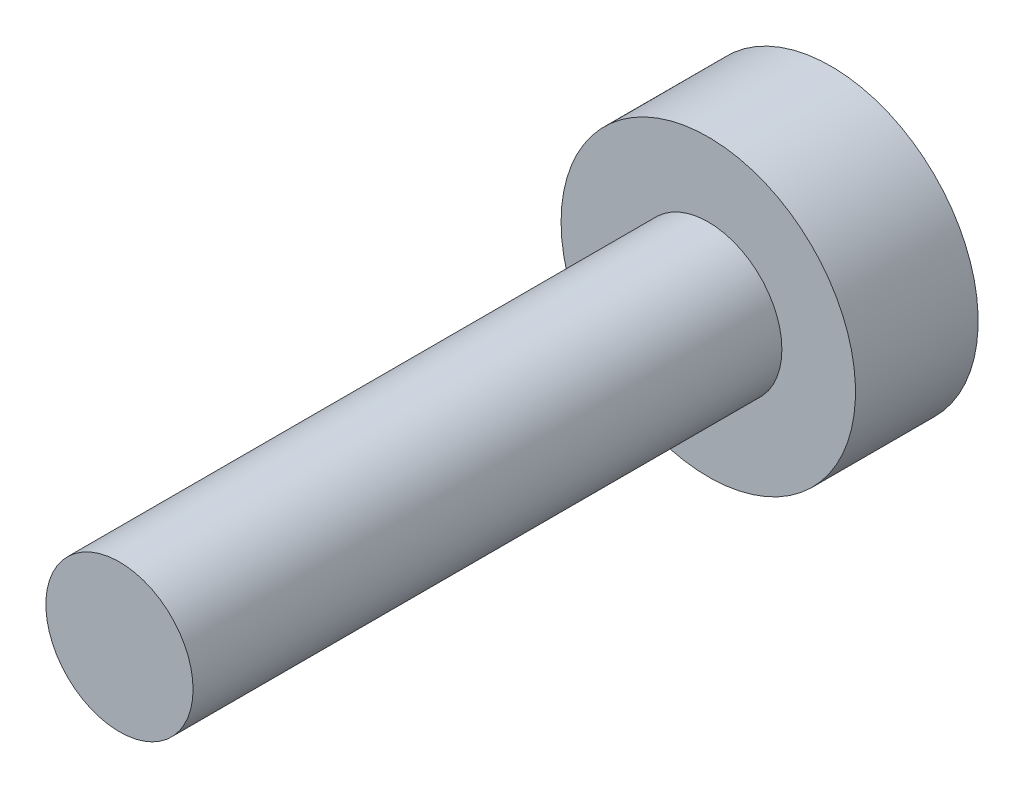
SolidWorks part; units mm, degrees
ref_plane "前视基准面" through (0, 0, 0) normal (0, 0, 1) x (1, 0, 0)
ref_plane "上视基准面" through (0, 0, 0) normal (0, 1, 0) x (1, 0, 0)
ref_plane "右视基准面" through (0, 0, 0) normal (1, 0, 0) x (0, 0, -1)
sketch "草图1" plane through (0, 0, 0) normal (0, 0, 1) x (1, 0, 0)
  circle A0 centre (-5.9441, 3.0062) radius 1.5
  dimension "D1" = 3
extrude "凸台-拉伸1" add sketch "草图1" along normal blind 12
sketch "草图2" plane through (0, 0, 0) normal (0, 0, -1) x (-1, 0, 0)
  circle A4 centre (5.9441, 3.0062) radius 3
  dimension "D1" = 6
extrude "凸台-拉伸2" add sketch "草图2" along normal blind 2.5
sketch "草图4" plane through (0, 0, -2.5) normal (0, 0, -1) x (-1, 0, 0)
  line L0 (2.9441, 3.0062) -> (8.9441, 3.0062) construction
  line L1 (5.9441, 6.0062) -> (5.9441, 0.0062) construction
  line L2 (8.0654, 0.8849) -> (3.8228, 5.1275) construction
  line L3 (3.9441, 3.2562) -> (5.6941, 3.2562)
  line L4 (3.9441, 3.2562) -> (3.9441, 2.7562)
  line L5 (3.9441, 2.7562) -> (5.6941, 2.7562)
  line L6 (7.9441, 3.2562) -> (7.9441, 2.7562)
  line L7 (6.1941, 5.0062) -> (6.1941, 3.2562)
  line L8 (5.6941, 1.0062) -> (6.1941, 1.0062)
  line L9 (5.6941, 5.0062) -> (5.6941, 3.2562)
  line L10 (5.6941, 5.0062) -> (6.1941, 5.0062)
  line L11 (5.6941, 2.7562) -> (5.6941, 1.0062)
  line L12 (6.1941, 2.7562) -> (7.9441, 2.7562)
  line L13 (6.1941, 2.7562) -> (6.1941, 1.0062)
  line L14 (6.1941, 3.2562) -> (7.9441, 3.2562)
  circle A0 centre (5.9441, 3.0062) radius 3 construction
  point P5 (5.9441, 3.0062)
  point P7 (5.9441, 3.0062)
  point P10 (5.9441, 3.0062)
  point P16 (5.9441, 3.0062)
  dimension "D1" = 4
  dimension "D2" = 2
  dimension "D3" = 0.5
  dimension "D4" = 0.25
extrude "切除-拉伸3" cut sketch "草图4" against normal blind 1 contours L3 L9 L10 L7 L14 L6 L12 L13 L8 L11 L5 L4
